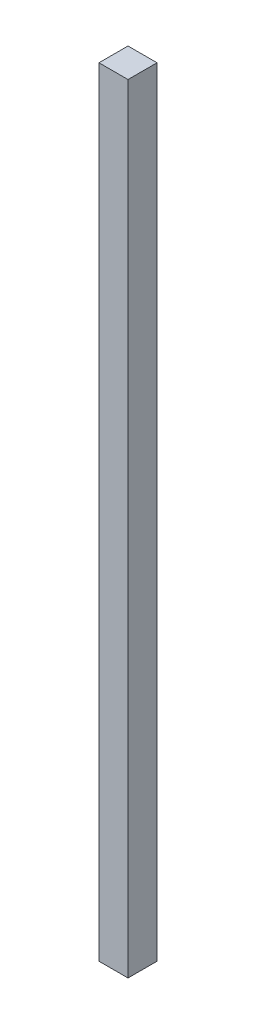
SolidWorks part; units mm, degrees
ref_plane "Front Plane" through (0, 0, 0) normal (0, 0, 1) x (1, 0, 0)
ref_plane "Top Plane" through (0, 0, 0) normal (0, 1, 0) x (1, 0, 0)
ref_plane "Right Plane" through (0, 0, 0) normal (1, 0, 0) x (0, 0, -1)
sketch "Sketch1" plane through (0, 0, 0) normal (0, 1, 0) x (1, 0, 0)
  line L1 (0, 0) -> (20, 0)
  line L2 (0, 0) -> (0, 20)
  line L3 (0, 20) -> (20, 20)
  line L4 (20, 0) -> (20, 20)
  dimension "D1" = 20
  dimension "D2" = 20
extrude "Boss-Extrude1" add sketch "Sketch1" along normal blind 536
